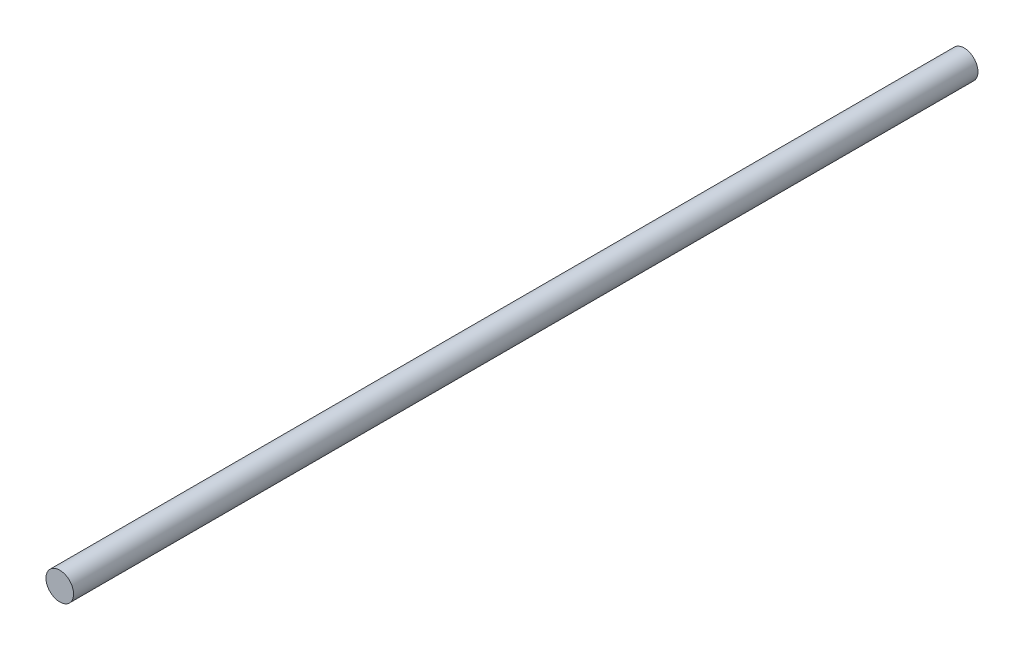
SolidWorks part; units mm, degrees
ref_plane "Front Plane" through (0, 0, 0) normal (0, 0, 1) x (1, 0, 0)
ref_plane "Top Plane" through (0, 0, 0) normal (0, 1, 0) x (1, 0, 0)
ref_plane "Right Plane" through (0, 0, 0) normal (1, 0, 0) x (0, 0, -1)
sketch "Sketch1" plane through (0, 0, 0) normal (0, 0, 1) x (1, 0, 0)
  circle A0 centre (0, 0) radius 5
  dimension "D1" = 10
extrude "Boss-Extrude1" add sketch "Sketch1" along normal blind 328
